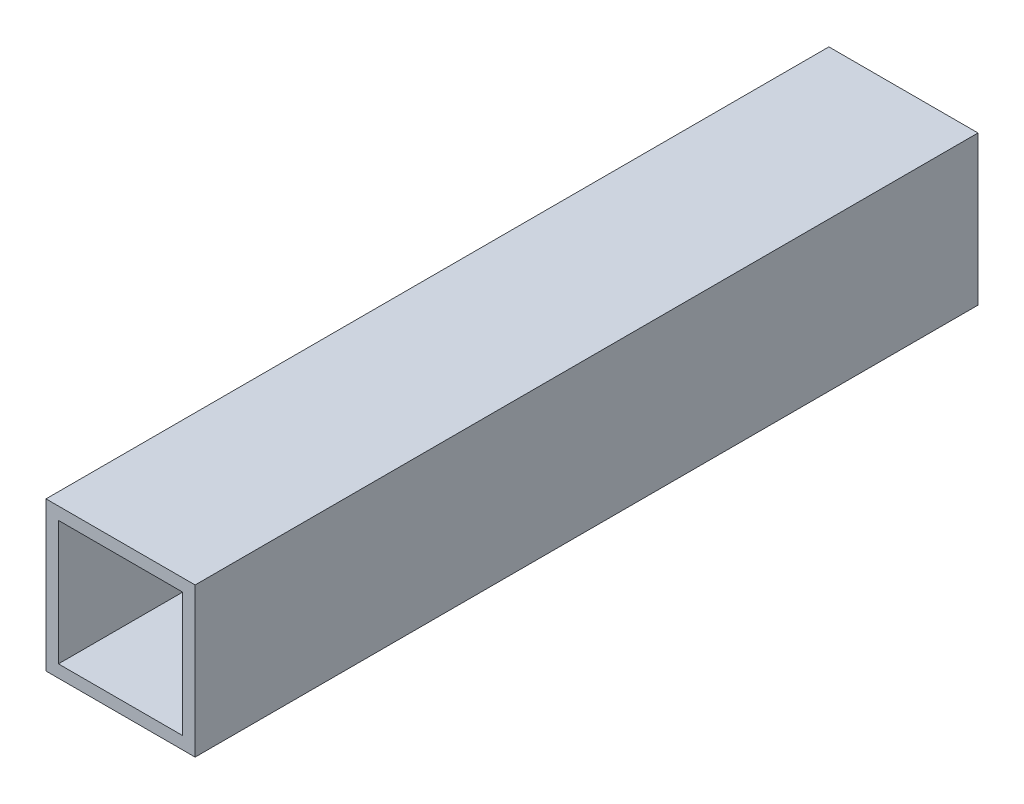
SolidWorks part; units mm, degrees
ref_plane "前视基准面" through (0, 0, 0) normal (0, 0, 1) x (1, 0, 0)
ref_plane "上视基准面" through (0, 0, 0) normal (0, 1, 0) x (1, 0, 0)
ref_plane "右视基准面" through (0, 0, 0) normal (1, 0, 0) x (0, 0, -1)
sketch "草图1" plane through (0, 0, 0) normal (0, 0, 1) x (1, 0, 0)
  line L0 (-12, 12) -> (12, 12)
  line L1 (-10, 10) -> (10, 10)
  line L2 (-10, 10) -> (-10, -10)
  line L3 (-10, -10) -> (10, -10)
  line L4 (10, 10) -> (10, -10)
  line L5 (-10, 10) -> (10, -10) construction
  line L6 (-10, -10) -> (10, 10) construction
  line L7 (12, 12) -> (12, -12)
  line L8 (-12, -12) -> (12, -12)
  line L9 (-12, 12) -> (-12, -12)
  point P0 (0, 0)
  dimension "D1" = 20
  dimension "D2" = 20
  dimension "D3" = 2
extrude "凸台-拉伸1" add sketch "草图1" along normal blind 126
